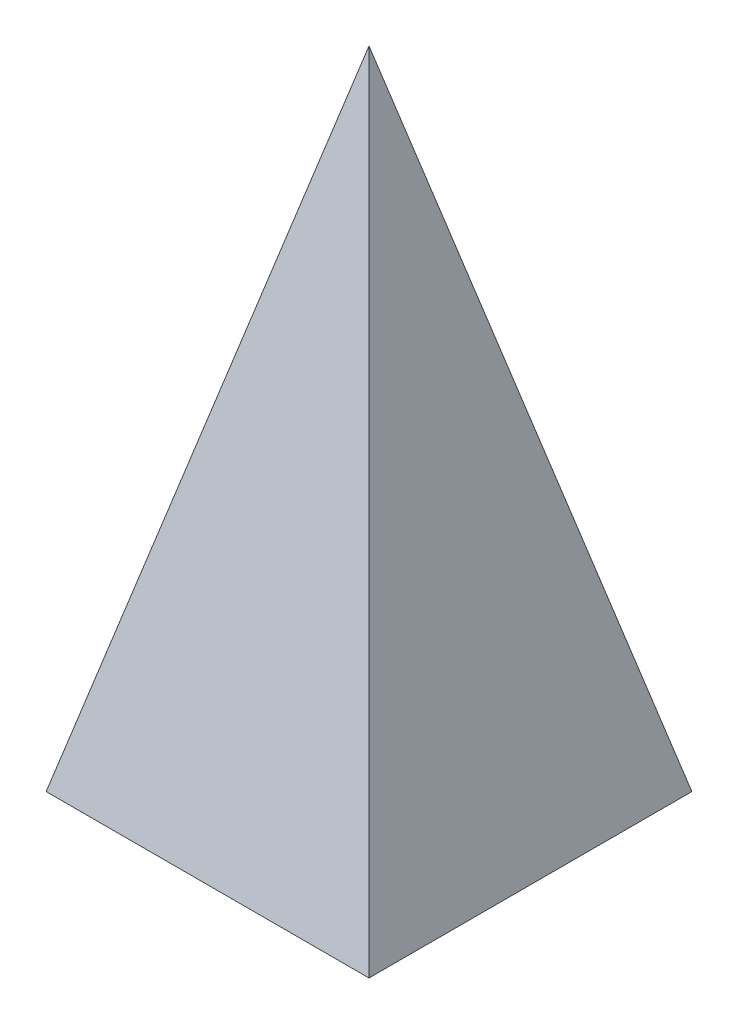
SolidWorks part; units mm, degrees
ref_plane "前视基准面" through (0, 0, 0) normal (0, 0, 1) x (1, 0, 0)
ref_plane "上视基准面" through (0, 0, 0) normal (0, 1, 0) x (1, 0, 0)
ref_plane "右视基准面" through (0, 0, 0) normal (1, 0, 0) x (0, 0, -1)
other "Configuration Table"
sketch "草图1" plane through (0, 0, 0) normal (0, 1, 0) x (1, 0, 0)
  line L1 (-10, 10) -> (10, 10)
  line L2 (-10, 10) -> (-10, -10)
  line L3 (-10, -10) -> (10, -10)
  line L4 (10, 10) -> (10, -10)
  line L5 (-10, 10) -> (10, -10) construction
  line L6 (-10, -10) -> (10, 10) construction
  point P6 (0, 0)
  point P7 (3.7779, -10)
  point P8 (0, 0)
  dimension "D1" = 20
  dimension "D2" = 20
ref_plane "基准面1" through (0, 40, 0) normal (0, 1, 0) x (1, 0, 0)
sketch "草图2" plane through (0, 40, 0) normal (0, 1, 0) x (1, 0, 0)
  point P0 (0, 0)
loft "放样1" add profiles "草图2", "草图1"
